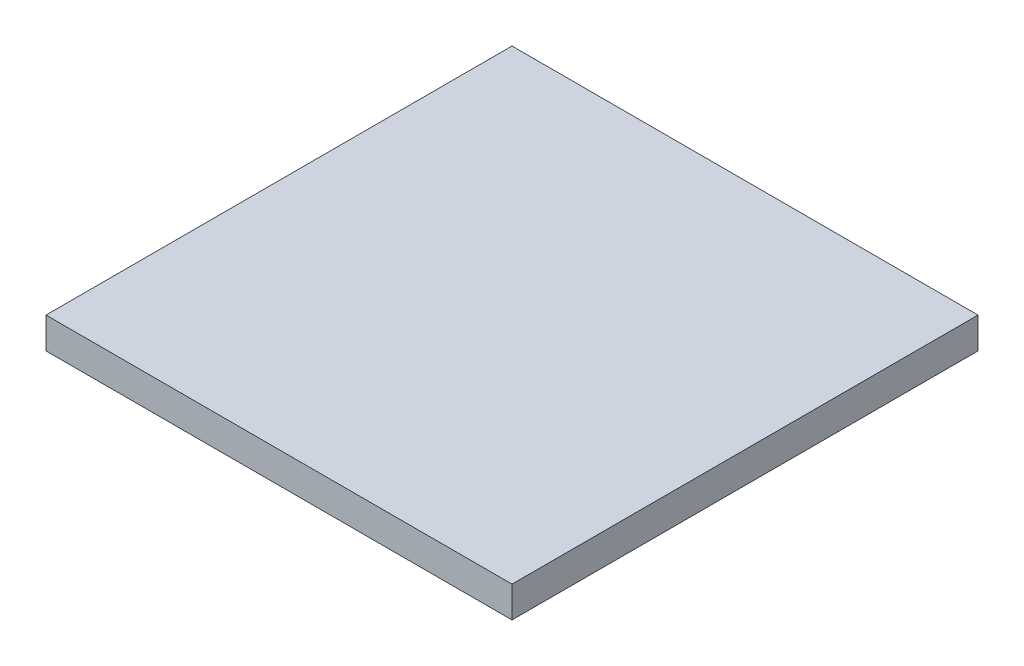
SolidWorks part; units mm, degrees
ref_plane "Front Plane" through (0, 0, 0) normal (0, 0, 1) x (1, 0, 0)
ref_plane "Top Plane" through (0, 0, 0) normal (0, 1, 0) x (1, 0, 0)
ref_plane "Right Plane" through (0, 0, 0) normal (1, 0, 0) x (0, 0, -1)
sketch "Sketch1" plane through (0, 0, 0) normal (0, 1, 0) x (1, 0, 0)
  line L1 (-150, -150) -> (150, -150)
  line L2 (-150, -150) -> (-150, 150)
  line L3 (-150, 150) -> (150, 150)
  line L4 (150, -150) -> (150, 150)
  line L5 (-150, -150) -> (150, 150) construction
  line L6 (-150, 150) -> (150, -150) construction
  point P0 (0, 0)
extrude "Boss-Extrude1" add sketch "Sketch1" along normal blind 20 contours L2 L1 L4 L3
